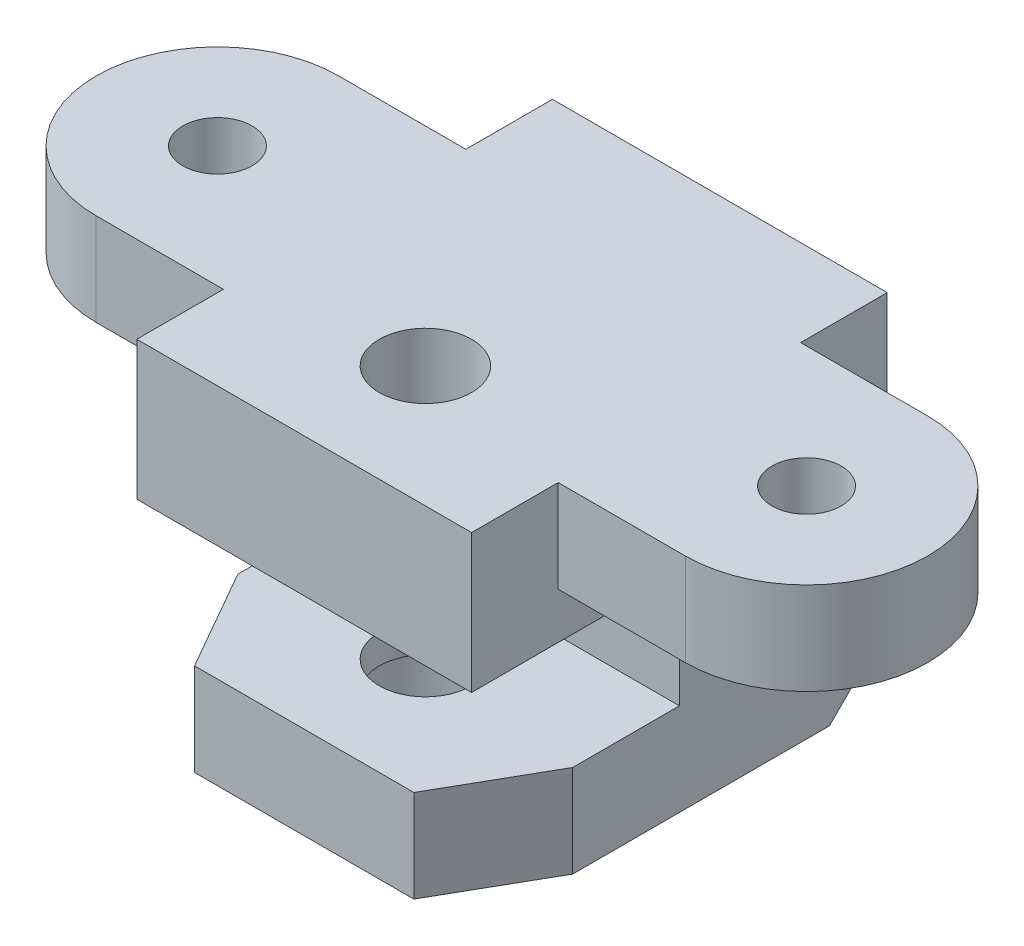
SolidWorks part; units mm, degrees
ref_plane "前视基准面" through (0, 0, 0) normal (0, 0, 1) x (1, 0, 0)
ref_plane "上视基准面" through (0, 0, 0) normal (0, 1, 0) x (1, 0, 0)
ref_plane "右视基准面" through (0, 0, 0) normal (1, 0, 0) x (0, 0, -1)
other "Configuration Table"
sketch "草图1" plane through (0, 0, 0) normal (0, 1, 0) x (1, 0, 0)
  line L1 (-58, -72) -> (58, -72)
  line L2 (-58, -72) -> (-58, 72)
  line L3 (-58, 72) -> (58, 72)
  line L4 (58, -72) -> (58, 72)
  line L5 (-58, -72) -> (58, 72) construction
  line L6 (-58, 72) -> (58, -72) construction
  point P0 (0, 0)
  point P5 (0, 0)
  dimension "D1" = 116
  dimension "D2" = 144
extrude "凸台-拉伸1" add sketch "草图1" against normal blind 120 contours L2 L1 L4 L3
sketch "草图2" plane through (0, 0, 0) normal (0, 1, 0) x (1, 0, 0)
  line L5 (-58, 42) -> (-102.0693, 42)
  line L6 (-58, -72) -> (-58, 72) construction
  line L7 (-102.0693, -42) -> (-58, -42)
  line L8 (-58, 42) -> (-58, -42)
  arc A0 (-102.0693, 42) -> (-102.0693, -42) centre (-102.0693, 0) ccw
  circle A1 centre (-102.0693, 0) radius 12
  dimension "D2" = 42
  dimension "D3" = 24
  dimension "D1" = 72
extrude "凸台-拉伸3" add sketch "草图2" against normal blind 32
sketch "草图6" plane through (-58, 0, 0) normal (-1, 0, 0) x (0, 0, 1)
  line L0 (72, -48) -> (0, -48)
  line L1 (72, -120) -> (72, 0) construction
  line L2 (0, -48) -> (0, -88)
  line L3 (0, -88) -> (72, -88)
  line L4 (72, -48) -> (72, -88)
  dimension "D1" = 48
  dimension "D2" = 32
extrude "切除-拉伸1" cut sketch "草图6" against normal through all
sketch "草图8" plane through (0, -120, 0) normal (0, -1, 0) x (1, 0, 0)
  line L0 (-38, 72) -> (-58, 37)
  line L1 (-58, 72) -> (58, 72) construction
  line L2 (-58, 72) -> (-58, -72) construction
  line L3 (-38, 72) -> (-58, 72)
  line L4 (-58, 72) -> (-58, 37)
  dimension "D1" = 20
  dimension "D2" = 35
extrude "切除-拉伸3" cut sketch "草图8" against normal up to next
mirror "镜向1" about plane through (0, 0, 0) normal (1, 0, 0) of "切除-拉伸3", "凸台-拉伸3"
sketch "草图9" plane through (-58, 0, 0) normal (-1, 0, 0) x (0, 0, 1)
  line L0 (-72, -100) -> (-52, -120)
  line L1 (-72, -120) -> (-72, 0) construction
  line L2 (37, -120) -> (-72, -120) construction
  line L3 (-52, -120) -> (-72, -120)
  line L4 (-72, -120) -> (-72, -100)
  dimension "D1" = 20
  dimension "D2" = 20
extrude "切除-拉伸4" cut sketch "草图9" against normal up to next
sketch "草图10" plane through (0, 0, 0) normal (0, 1, 0) x (1, 0, 0)
  line L0 (-58, -72) -> (58, -72) construction
  circle A0 centre (0, -30) radius 16
  dimension "D2" = 32
  dimension "D1" = 42
extrude "切除-拉伸5" cut sketch "草图10" against normal through all
sketch "草图11" plane through (0, -120, 0) normal (0, -1, 0) x (1, 0, 0)
  circle A0 centre (0, 30) radius 27
  dimension "D1" = 54
extrude "切除-拉伸6" cut sketch "草图11" against normal blind 22
